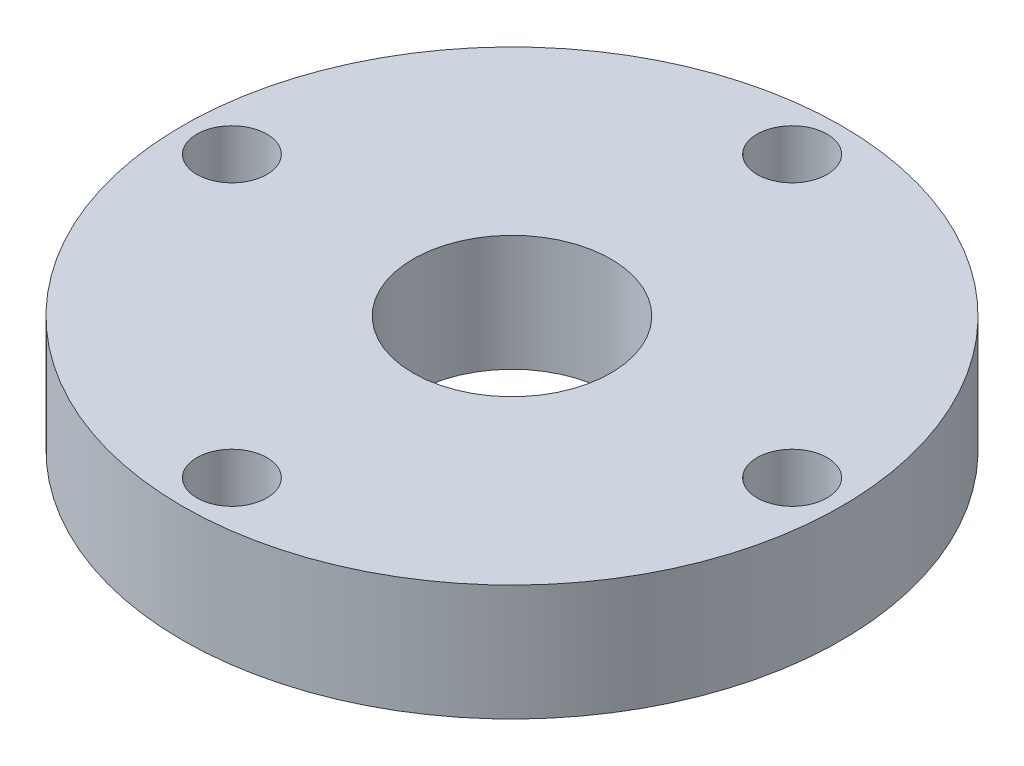
SolidWorks part; units mm, degrees
ref_plane "Front Plane" through (0, 0, 0) normal (1, 0, 0) x (0, 1, 0)
ref_plane "Top Plane" through (0, 0, 0) normal (0, 0, 1) x (0, 1, 0)
ref_plane "Right Plane" through (0, 0, 0) normal (0, 1, 0) x (-1, 0, 0)
sketch "Sketch1" plane through (0, 0, 0) normal (0, 0, 1) x (0, 1, 0)
  line L0 (-11.176, 0) -> (-11.176, 63.5)
  line L1 (-11.176, 63.5) -> (11.176, 63.5)
  line L2 (11.176, 63.5) -> (11.176, 0)
  line L3 (11.176, 0) -> (-11.176, 0)
  line L4 (-36.576, 0) -> (36.576, 0) construction
  dimension "D1" = 22.352
  dimension "D2" = 63.5
revolve "Revolve1" add sketch "Sketch1" angle 360 about L4
sketch "Sketch2" plane through (0, 0, 0) normal (0, 1, 0) x (-1, 0, 0)
  circle A0 centre (0, 0) radius 19.05
  dimension "D1" = 38.1
extrude "Cut-Extrude2" cut sketch "Sketch2" against normal through all from offset 11.176
hole_wizard "CBORE for 5/16 Socket Head Cap Screw1" positions "Sketch4" profile "Sketch3" counterbore size "5/16" standard "ANSI Inch"
sketch "Sketch4" plane through (0, 11.176, 0) normal (0, 1, 0) x (1, 0, 0)
  circle A0 centre (0, 0) radius 53.975 construction
  circle A1 centre (0, 0) radius 19.05 construction
  point P0 (-53.975, 0)
  point P1 (0, -53.975)
  point P3 (53.975, 0)
  point P5 (0, 53.975)
  dimension "D1" = 107.95
  dimension "D2" = 53.975
  dimension "D3" = 53.975
  dimension "D4" = 53.975
  dimension "D5" = 53.975
sketch "Sketch3" plane through (-53.975, 11.176, 0) normal (1, 0, 0) x (0, 0, 1)
  line L0 (0, 0) -> (0, 24.977)
  line L1 (0, 24.977) -> (4.3688, 22.352)
  line L2 (4.3688, 22.352) -> (4.3688, 9.652)
  line L3 (4.3688, 9.652) -> (6.7437, 9.652)
  line L4 (6.7437, 9.652) -> (6.7437, 0)
  line L5 (6.7437, 0) -> (0, 0)
  line L10 (0, 24.977) -> (-4.3688, 22.352) construction
  line L11 (0, -6.35) -> (0, 107.95) construction
  dimension "Hole Dia." = 8.7376
  dimension "Hole Depth" = 22.352
  dimension "C'Bore Dia." = 13.4874
  dimension "C'Bore Depth" = 9.652
  dimension "Drill Angle" = 118
